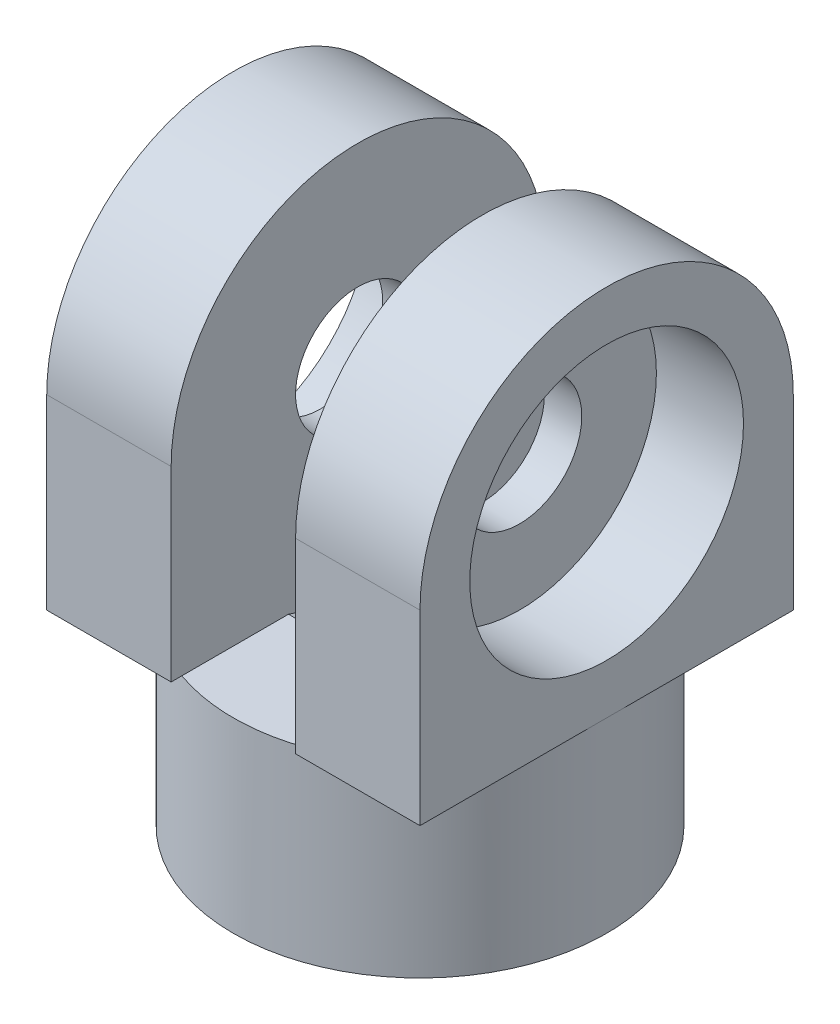
SolidWorks part; units mm, degrees
ref_plane "Front Plane" through (0, 0, 0) normal (0, 0, 1) x (1, 0, 0)
ref_plane "Top Plane" through (0, 0, 0) normal (0, 1, 0) x (1, 0, 0)
ref_plane "Right Plane" through (0, 0, 0) normal (1, 0, 0) x (0, 0, -1)
sketch "Sketch1" plane through (0, 0, 0) normal (0, 1, 0) x (1, 0, 0)
  circle A0 centre (0, 0) radius 15
  dimension "D1" = 30
extrude "Boss-Extrude1" add sketch "Sketch1" along normal blind 30
sketch "Sketch8" plane through (0, 30, 0) normal (0, 1, 0) x (1, 0, 0)
  line L0 (-55, 0) -> (55, 0) construction
  line L1 (15, 0) -> (-15, 0)
  line L2 (15, 0) -> (15, -15)
  line L3 (15, -15) -> (-15, -15)
  line L4 (-15, 0) -> (-15, -15)
  circle A0 centre (0, 0) radius 15 construction
  dimension "D1" = 15
  dimension "D2" = 30
revolve "Revolve1" add sketch "Sketch8" angle 180 about L1
sketch "Sketch9" plane through (0, 30, 0) normal (0, -1, 0) x (1, 0, 0)
  line L1 (15, 15) -> (-15, 15)
  line L2 (15, 15) -> (15, -15)
  line L3 (15, -15) -> (-15, -15)
  line L4 (-15, 15) -> (-15, -15)
extrude "Boss-Extrude3" add sketch "Sketch9" along normal blind 15
sketch "Sketch10" plane through (15, 0, 0) normal (1, 0, 0) x (0, 0, -1)
  circle A0 centre (0, 30) radius 5
  dimension "D1" = 10
extrude "Cut-Extrude1" cut sketch "Sketch10" against normal blind 30
ref_plane "Plane1" through (5, 0, 0) normal (1, 0, 0) x (0, 0, -1)
sketch "Sketch13" plane through (5, 0, 0) normal (1, 0, 0) x (0, 0, -1)
  line L0 (0, 16.5) -> (0, -16.5) construction
  line L1 (15, 15) -> (0, 15) construction
  circle A0 centre (0, 30) radius 16
  dimension "D1" = 32
  dimension "D2" = 15
extrude "Cut-Extrude2" cut sketch "Sketch13" against normal blind 10
sketch "Sketch14" plane through (0, 0, 15) normal (0, 0, 1) x (1, 0, 0)
  line L0 (5, -16.5) -> (5, 16.5) construction
  line L1 (-5, 30) -> (5, 30)
  line L2 (-5, 30) -> (-5, 15)
  line L3 (-5, 15) -> (5, 15)
  line L4 (5, 30) -> (5, 15)
  line L5 (0, 15) -> (15, 15) construction
extrude "Cut-Extrude3" cut sketch "Sketch14" against normal blind 67
sketch "Sketch15" plane through (-15, 0, 0) normal (-1, 0, 0) x (0, 0, 1)
  circle A0 centre (0, 30) radius 5 construction
  circle A1 centre (0, 30) radius 5
  circle A2 centre (0, 30) radius 11
  dimension "D1" = 22
extrude "Cut-Extrude4" cut sketch "Sketch15" against normal blind 7
sketch "Sketch16" plane through (15, 0, 0) normal (1, 0, 0) x (0, 0, -1)
  circle A0 centre (0, 30) radius 5 construction
  circle A1 centre (0, 30) radius 5
  circle A2 centre (0, 30) radius 11
  dimension "D1" = 22
extrude "Cut-Extrude5" cut sketch "Sketch16" against normal blind 7
